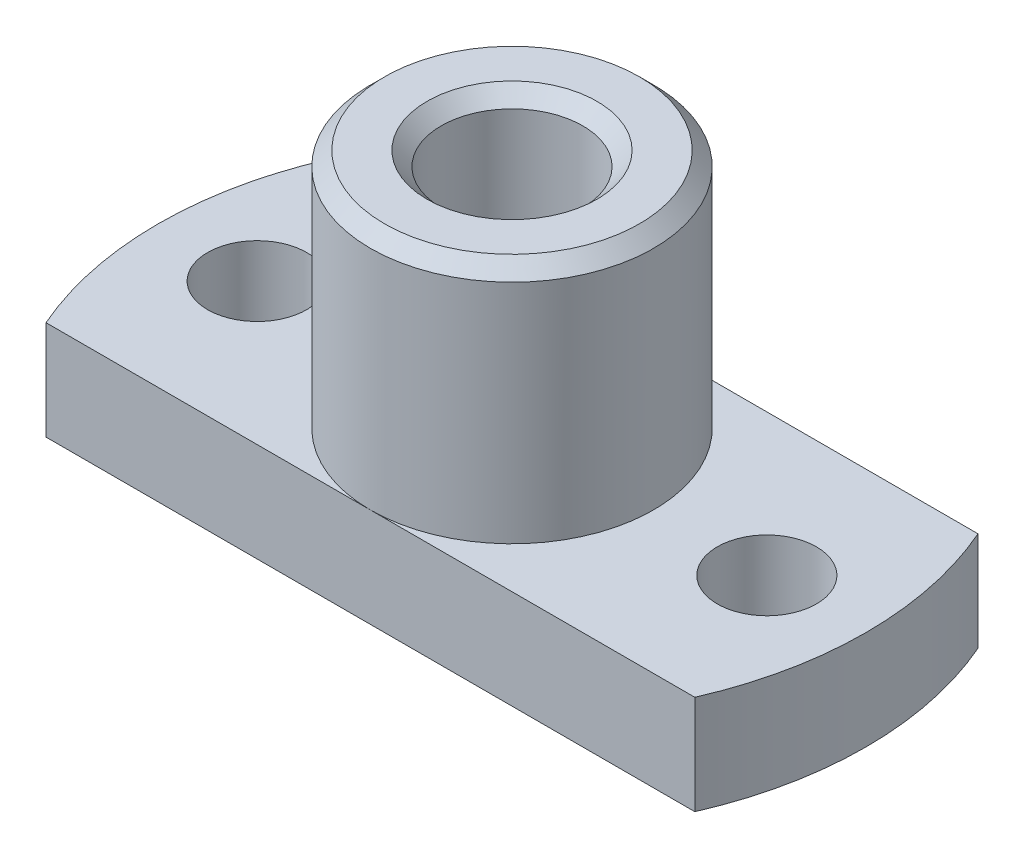
SolidWorks part; units mm, degrees
ref_plane "前视基准面" through (0, 0, 0) normal (0, 0, 1) x (1, 0, 0)
ref_plane "上视基准面" through (0, 0, 0) normal (0, 1, 0) x (1, 0, 0)
ref_plane "右视基准面" through (0, 0, 0) normal (1, 0, 0) x (0, 0, -1)
other "Configuration Table"
sketch "草图1" plane through (0, 0, 0) normal (0, 1, 0) x (1, 0, 0)
  line L0 (-12.5, 0) -> (12.5, 0) construction
  line L1 (-11.4564, 5) -> (11.4564, 5)
  line L2 (-11.4564, -5) -> (11.4564, -5)
  circle A0 centre (0, 0) radius 12.5
  dimension "D1" = 25
  dimension "D2" = 5
extrude "凸台-拉伸1" add sketch "草图1" along normal blind 3.5 contours A0 L0 L1 | L0 A0 L2
sketch "草图2" plane through (0, 3.5, 0) normal (0, 1, 0) x (1, 0, 0)
  circle A0 centre (0, 0) radius 5
  dimension "D1" = 10
extrude "凸台-拉伸2" add sketch "草图2" along normal blind 8.5
sketch "草图3" plane through (0, 12, 0) normal (0, 1, 0) x (1, 0, 0)
  circle A0 centre (0, 0) radius 2.5
  dimension "D1" = 5
extrude "切除-拉伸1" cut sketch "草图3" against normal through all
sketch "草图4" plane through (0, 3.5, 0) normal (0, 1, 0) x (1, 0, 0)
  line L0 (0, 0) -> (-9, 0) construction
  line L1 (0, 2.5) -> (0, -2.5) construction
  circle A0 centre (-9, 0) radius 1.75
  circle A1 centre (0, 0) radius 2.5 construction
  circle A2 centre (9, 0) radius 1.75
  dimension "D1" = 3.5
  dimension "D2" = 9
extrude "切除-拉伸2" cut sketch "草图4" against normal through all
chamfer "倒角1" distance 0.5 angle 45 2 edges at (0, 12, 5) (0, 12, 2.5)
